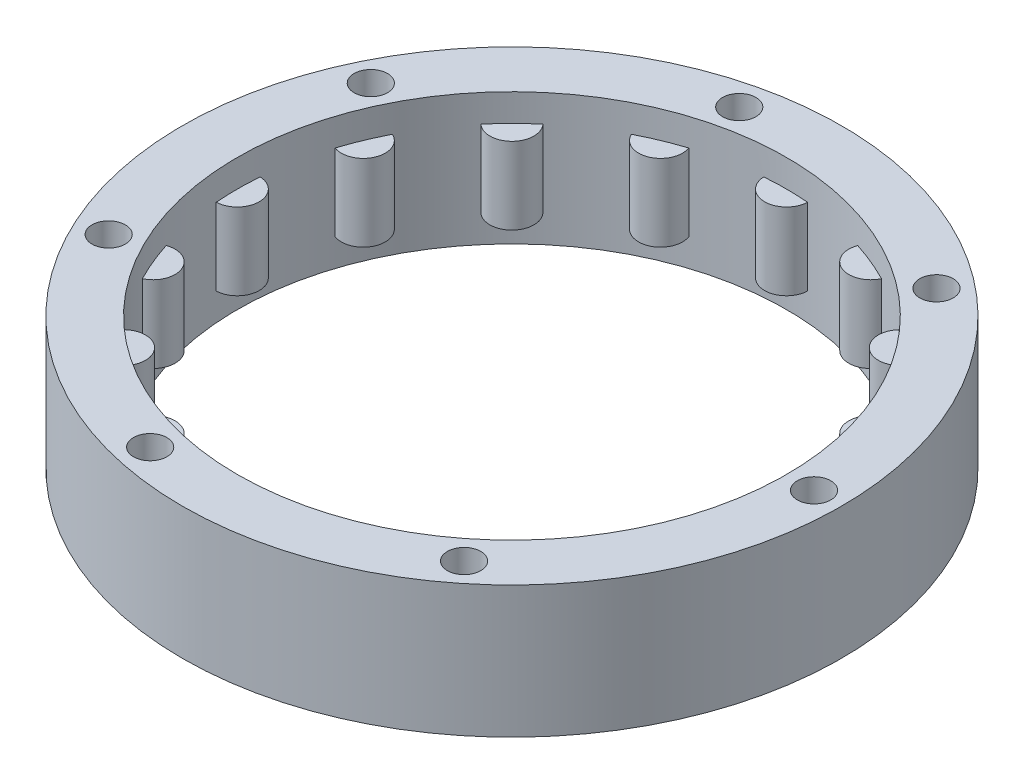
SolidWorks part; units mm, degrees
ref_plane "Alzado" through (0, 0, 0) normal (0, 0, 1) x (1, 0, 0)
ref_plane "Planta" through (0, 0, 0) normal (0, 1, 0) x (1, 0, 0)
ref_plane "Vista lateral" through (0, 0, 0) normal (1, 0, 0) x (0, 0, -1)
sketch "Croquis1" plane through (0, 0, 0) normal (0, 1, 0) x (1, 0, 0)
  circle A0 centre (0, 0) radius 25 construction
  circle A1 centre (25, 0) radius 2
  circle A2 centre (23.097, -9.5671) radius 2
  circle A3 centre (17.6777, -17.6777) radius 2
  circle A4 centre (9.5671, -23.097) radius 2
  circle A5 centre (0, -25) radius 2
  circle A6 centre (-9.5671, -23.097) radius 2
  circle A7 centre (-17.6777, -17.6777) radius 2
  circle A8 centre (-23.097, -9.5671) radius 2
  circle A9 centre (-25, 0) radius 2
  circle A10 centre (-23.097, 9.5671) radius 2
  circle A11 centre (-17.6777, 17.6777) radius 2
  circle A12 centre (-9.5671, 23.097) radius 2
  circle A13 centre (0, 25) radius 2
  circle A14 centre (9.5671, 23.097) radius 2
  circle A15 centre (17.6777, 17.6777) radius 2
  circle A16 centre (23.097, 9.5671) radius 2
  point P37 (0, 0)
  dimension "D1" = 50
  dimension "D2" = 4
  dimension "D3" = 16
extrude "Saliente-Extruir1" add sketch "Croquis1" along normal mid plane 7
sketch "Croquis3" plane through (0, 0, 0) normal (0, 1, 0) x (1, 0, 0)
  circle A0 centre (0, 0) radius 25
  circle A1 centre (0, 0) radius 30
  dimension "D1" = 60
extrude "Saliente-Extruir2" add sketch "Croquis3" along normal mid plane 12
sketch "Croquis4" plane through (0, 6, 0) normal (0, 1, 0) x (1, 0, 0)
  circle A0 centre (27.5, 0) radius 1.52
  circle A1 centre (17.146, -21.5004) radius 1.52
  circle A2 centre (-6.1193, -26.8105) radius 1.52
  circle A3 centre (-24.7766, -11.9318) radius 1.52
  circle A4 centre (-24.7766, 11.9318) radius 1.52
  circle A5 centre (-6.1193, 26.8105) radius 1.52
  circle A6 centre (17.146, 21.5004) radius 1.52
  point P17 (0, 0)
  dimension "D2" = 3.04
  dimension "D1" = 27.5
  dimension "D3" = 7
extrude "Cortar-Extruir1" cut sketch "Croquis4" against normal through all
